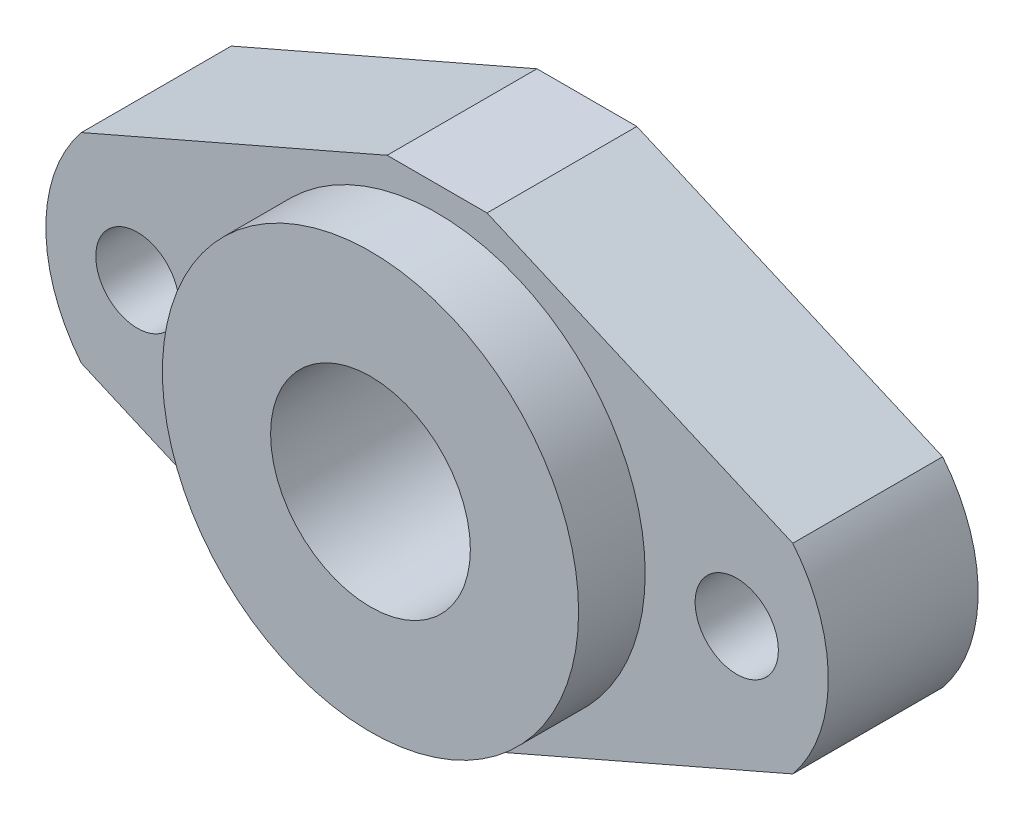
SolidWorks part; units mm, degrees
ref_plane "Front Plane" through (0, 0, 0) normal (0, 0, 1) x (1, 0, 0)
ref_plane "Top Plane" through (0, 0, 0) normal (0, 1, 0) x (1, 0, 0)
ref_plane "Right Plane" through (0, 0, 0) normal (1, 0, 0) x (0, 0, -1)
sketch "Sketch1" plane through (0, 0, 0) normal (0, 0, 1) x (1, 0, 0)
  line L0 (-18, 0) -> (18, 0) construction
  line L1 (-18, 0) -> (-23.5, 0) construction
  line L2 (-23.5, 0) -> (-23.5, 6) construction
  line L3 (-21.3655, 6) -> (-3, 14)
  line L4 (-3, 14) -> (3, 14)
  line L5 (-21.3655, -6) -> (-3, -14)
  line L6 (-3, -14) -> (3, -14)
  line L7 (0, 0) -> (0, 14) construction
  line L8 (21.3655, -6) -> (3, -14)
  line L9 (21.3655, 6) -> (3, 14)
  circle A0 centre (-18, 0) radius 2.5
  circle A1 centre (18, 0) radius 2.5
  circle A2 centre (0, 0) radius 6
  arc A3 (-21.3655, -6) -> (-21.3655, 6) centre (-14, 0) cw
  circle A4 centre (18, 0) radius 2.5
  arc A5 (21.3655, -6) -> (21.3655, 6) centre (14, 0) ccw
  point P4 (0, 0)
  point P13 (0, -14)
  dimension "D2" = 5
  dimension "D3" = 12
  dimension "D5" = 23.5
  dimension "D6" = 4
  dimension "D1" = 36
  dimension "D4" = 6
  dimension "D7" = 3
  dimension "D8" = 28
extrude "Boss-Extrude1" add sketch "Sketch1" along normal blind 9 contours L8 A5 L9 L4 L3 A3 L5 L6 A0 A1 A2
sketch "Sketch2" plane through (0, 0, 9) normal (0, 0, 1) x (1, 0, 0)
  circle A0 centre (0, 0) radius 6
  circle A1 centre (0, 0) radius 6 construction
  circle A2 centre (0, 0) radius 12.5
  dimension "D1" = 25
extrude "Boss-Extrude2" add sketch "Sketch2" along normal blind 4
